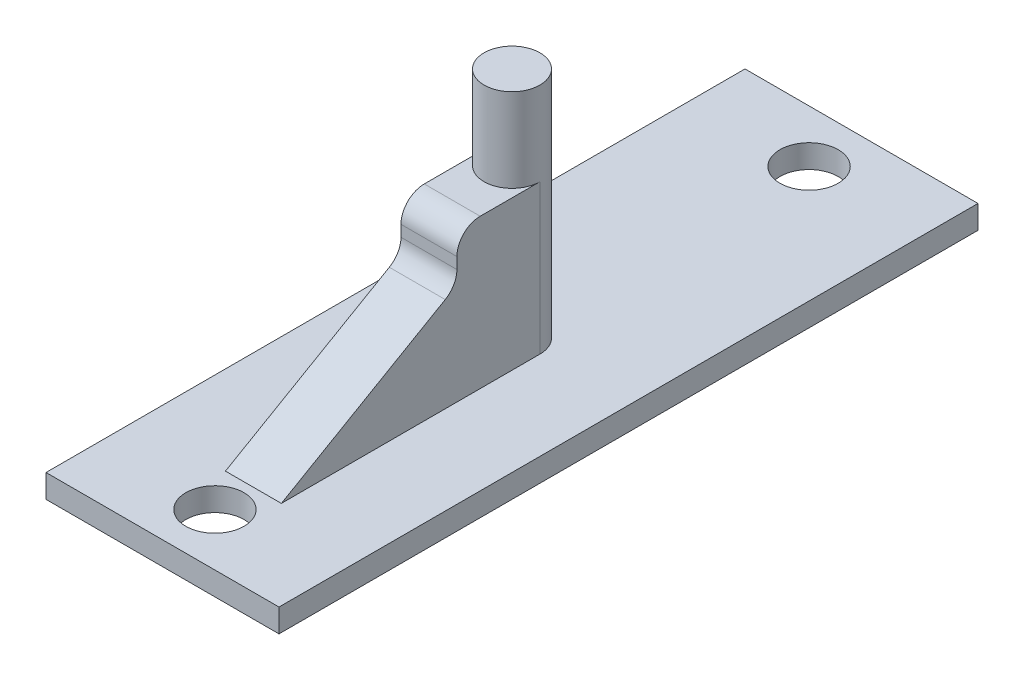
SolidWorks part; units mm, degrees
ref_plane "Front Plane" through (0, 0, 0) normal (0, 0, 1) x (1, 0, 0)
ref_plane "Top Plane" through (0, 0, 0) normal (0, 1, 0) x (1, 0, 0)
ref_plane "Right Plane" through (0, 0, 0) normal (1, 0, 0) x (0, 0, -1)
sketch "Sketch1" plane through (0, 0, 0) normal (0, 1, 0) x (1, 0, 0)
  line L1 (-10, 30) -> (10, 30)
  line L2 (-10, 30) -> (-10, -30)
  line L3 (-10, -30) -> (10, -30)
  line L4 (10, 30) -> (10, -30)
  point P4 (0, 30)
  point P6 (10, 0)
  dimension "D1" = 20
  dimension "D2" = 60
extrude "Boss-Extrude1" add sketch "Sketch1" along normal blind 2
sketch "Sketch2" plane through (0, 2, 0) normal (0, 1, 0) x (1, 0, 0)
  line L0 (-10, 0) -> (10, 0) construction
  line L1 (-10, 30) -> (-10, -30) construction
  line L2 (10, -30) -> (10, 30) construction
  line L3 (10, 30) -> (-10, 30) construction
  line L4 (0, 30) -> (0, -30) construction
  line L5 (-10, -30) -> (10, -30) construction
  circle A0 centre (0, 25.5) radius 2.5
  circle A1 centre (0, -25.5) radius 2.5
  dimension "D1" = 5
  dimension "D2" = 4.5
extrude "Cut-Extrude1" cut sketch "Sketch2" against normal through all
sketch "Sketch3" plane through (0, 2, 0) normal (0, 1, 0) x (1, 0, 0)
  circle A0 centre (0, 0) radius 2.4
  dimension "D1" = 4.8
extrude "Boss-Extrude2" add sketch "Sketch3" along normal blind 20
ref_plane "Plane1" through (-2.4, 0, 0) normal (-1, 0, 0) x (0, 0, 1)
sketch "Sketch4" plane through (-2.4, 0, 0) normal (-1, 0, 0) x (0, 0, 1)
  line L0 (8.1308, 10.1208) -> (22.1964, 2)
  line L2 (-30, 2) -> (30, 2) construction
  line L6 (22.1964, 2) -> (0, 2)
  line L7 (0, 2) -> (0, 14.8151)
  line L8 (0, 14.8151) -> (0, 2) construction
  line L10 (0, 14.8151) -> (5.1308, 14.8151)
  line L11 (7.1308, 12.8151) -> (7.1308, 11.8528)
  arc A0 (7.1308, 12.8151) -> (5.1308, 14.8151) centre (5.1308, 12.8151) ccw
  arc A1 (8.1308, 10.1208) -> (7.1308, 11.8528) centre (9.1308, 11.8528) cw
  dimension "D2" = 2
  dimension "D1" = 30
extrude "Boss-Extrude7" add sketch "Sketch4" against normal blind 4.8
sketch "Sketch5" plane through (0, 0, 0) normal (0, 0, 1) x (1, 0, 0)
  line L0 (0, 1.7732) -> (0, 22.2591) construction
  line L1 (2.4, 22) -> (-2.4, 22) construction
  circle A0 centre (0, 21.3) radius 0.5
  dimension "D1" = 1
  dimension "D2" = 0.7
extrude "Cut-Extrude2" cut sketch "Sketch5" against normal blind 2 from offset 1
equation "\"holderWidth\"=20"
equation "\"D1@Sketch1\"=\"holderWidth\""
equation "\"holderHeight\"=60"
equation "\"D2@Sketch1\"=\"holderHeight\""
equation "\"holderDepth\"=2"
equation "\"D1@Boss-Extrude1\"=\"holderDepth\""
equation "\"screwDiameter\"=5"
equation "\"D1@Sketch2\"=\"screwDiameter\""
equation "\"D2@Sketch2\"=(\"screwDiameter\"/2) +2"
equation "\"pulleyAxisDiameter\"=4.8"
equation "\"D1@Sketch3\"=\"pulleyAxisDiameter\""
equation "\"D1@Boss-Extrude7\"=\"pulleyAxisDiameter\""
equation "\"lockPinHoleDiameter\"=1"
equation "\"D1@Sketch5\"=\"lockPinHoleDiameter\""
